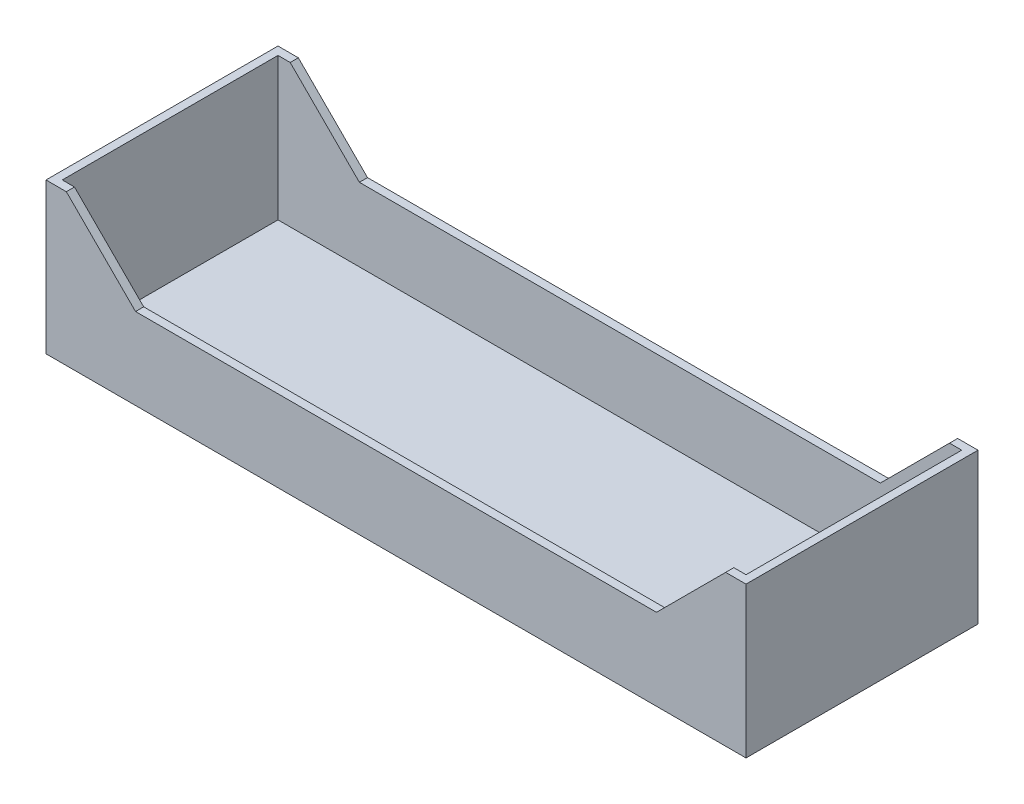
SolidWorks part; units mm, degrees
ref_plane "前视基准面" through (0, 0, 0) normal (0, 0, 1) x (1, 0, 0)
ref_plane "上视基准面" through (0, 0, 0) normal (0, 1, 0) x (1, 0, 0)
ref_plane "右视基准面" through (0, 0, 0) normal (1, 0, 0) x (0, 0, -1)
sketch "草图1" plane through (0, 0, 0) normal (0, 1, 0) x (1, 0, 0)
  line L0 (0, 28.5) -> (0, -59.0518) construction
  line L1 (-86, -28.5) -> (86, -28.5)
  line L2 (-86, -28.5) -> (-86, 28.5)
  line L3 (-86, 28.5) -> (86, 28.5)
  line L4 (86, -28.5) -> (86, 28.5)
  line L5 (-86, 0) -> (86, 0) construction
  point P5 (0, 0)
  dimension "D1" = 172
  dimension "D2" = 57
extrude "凸台-拉伸1" add sketch "草图1" along normal blind 2
sketch "草图3" plane through (0, 2, 0) normal (0, 1, 0) x (1, 0, 0)
  line L0 (-84, 26.5) -> (84, 26.5)
  line L1 (-86, -28.5) -> (86, -28.5)
  line L2 (-86, -28.5) -> (-86, 28.5)
  line L3 (-86, 28.5) -> (86, 28.5)
  line L4 (86, -28.5) -> (86, 28.5)
  line L5 (84, -26.5) -> (84, 26.5)
  line L6 (-84, -26.5) -> (84, -26.5)
  line L7 (-84, -26.5) -> (-84, 26.5)
  line L8 (-86, 28.5) -> (-86, -28.5) construction
  line L9 (-86, -28.5) -> (86, -28.5) construction
  dimension "D1" = 2
extrude "凸台-拉伸2" add sketch "草图3" along normal blind 35
sketch "草图4" plane through (0, 0, 28.5) normal (0, 0, 1) x (1, 0, 0)
  line L0 (0, 37) -> (0, -12.9758) construction
  line L2 (-86, 37) -> (86, 37) construction
  line L3 (-81, 37) -> (-64, 20)
  line L4 (-64, 20) -> (64, 20)
  line L5 (-86, 0) -> (86, 0) construction
  line L6 (-81, 37) -> (81, 37)
  line L7 (-86, 37) -> (-86, 0) construction
  line L8 (81, 37) -> (64, 20)
  point P12 (0, 20)
  dimension "D1" = 45
  dimension "D2" = 20
  dimension "D3" = 5
extrude "切除-拉伸1" cut sketch "草图4" against normal through all
